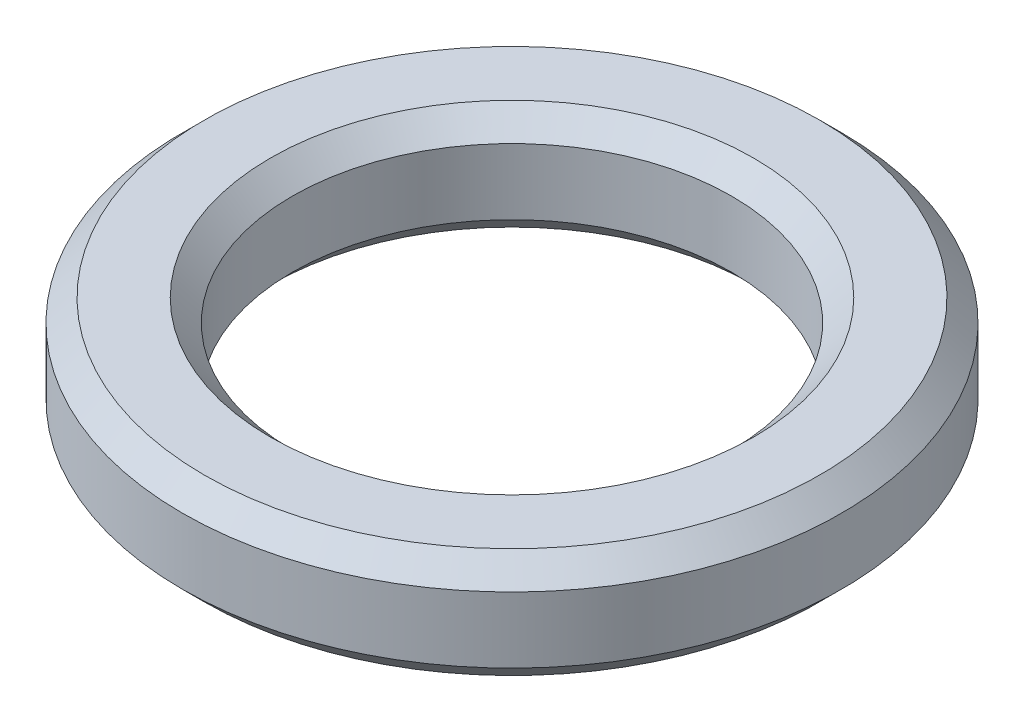
SolidWorks part; units mm, degrees
ref_plane "Front Plane" through (0, 0, 0) normal (0, 0, 1) x (1, 0, 0)
ref_plane "Top Plane" through (0, 0, 0) normal (0, 1, 0) x (1, 0, 0)
ref_plane "Right Plane" through (0, 0, 0) normal (1, 0, 0) x (0, 0, -1)
sketch "Sketch1" plane through (0, 0, 0) normal (0, 1, 0) x (1, 0, 0)
  circle A0 centre (0, 0) radius 10
  dimension "D1" = 20
extrude "Extrude-Thin1" add sketch "Sketch1" along normal blind 5 thin
chamfer "Chamfer1" distance 1 angle 45 4 edges at (15, 0, 0) (15, 5, 0) (0, 0, 10) (0, 5, 10)
